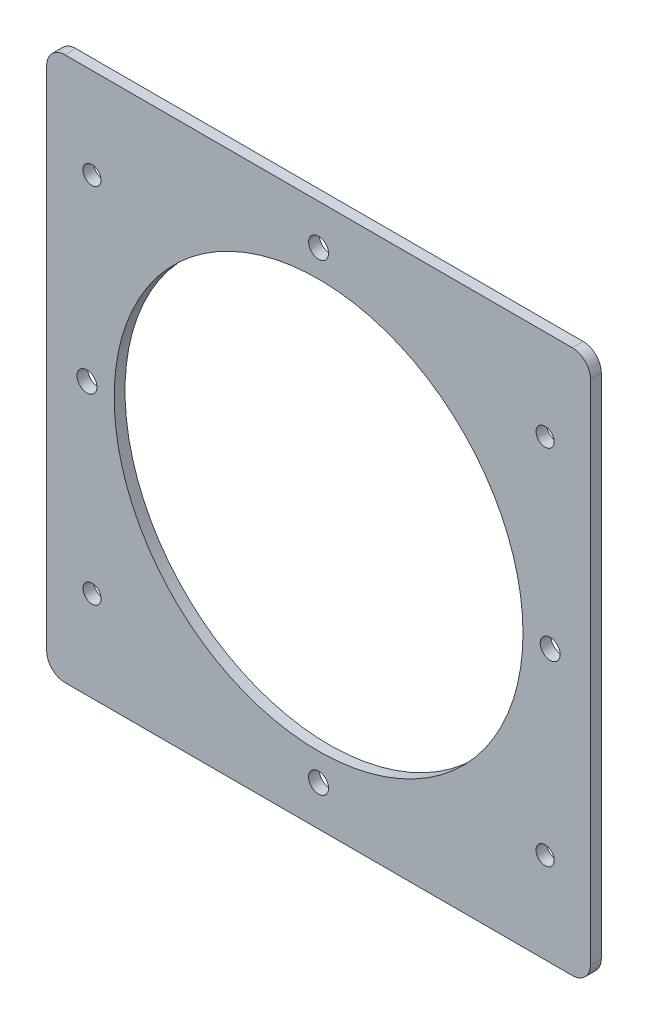
SolidWorks part; units mm, degrees
material "6061 Alloy"
ref_plane "Front Plane" through (0, 0, 0) normal (0, 0, 1) x (1, 0, 0)
ref_plane "Top Plane" through (0, 0, 0) normal (0, 1, 0) x (1, 0, 0)
ref_plane "Right Plane" through (0, 0, 0) normal (1, 0, 0) x (0, 0, -1)
sketch "Sketch1" plane through (0, 0, 0) normal (0, 0, 1) x (1, 0, 0)
  line L1 (-75, 75) -> (75, 75)
  line L2 (-75, 75) -> (-75, -75)
  line L3 (-75, -75) -> (75, -75)
  line L4 (75, 75) -> (75, -75)
  line L5 (0, -75) -> (0, 75) construction
  line L6 (-75, 0) -> (75, 0) construction
  point P0 (0, 0)
  dimension "D1" = 150
  dimension "D2" = 150
extrude "Boss-Extrude1" add sketch "Sketch1" along normal mid plane 3
sketch "Sketch2" plane through (0, 0, 0) normal (0, 0, 1) x (1, 0, 0)
  circle A0 centre (0, 0) radius 63.9 construction
  circle A1 centre (0, 63.9) radius 2.75
  circle A2 centre (63.9, 0) radius 2.75
  circle A3 centre (0, -63.9) radius 2.75
  circle A4 centre (-63.9, 0) radius 2.75
  point P14 (0, 0)
  dimension "D1" = 5.5
  dimension "D2" = 127.8
  dimension "D3" = 4
extrude "Cut-Extrude1" cut sketch "Sketch2" against normal through all both and the other way through all
sketch "Sketch3" plane through (0, 0, 0) normal (0, 0, 1) x (1, 0, 0)
  arc A0 (-56, -6.7052) -> (56, -6.7052) centre (0, 0) ccw
  arc A1 (56, -6.7052) -> (-56, -6.7052) centre (0, 0) ccw
  dimension "D1" = 112.8
extrude "Cut-Extrude2" cut sketch "Sketch3" against normal through all both and the other way through all
sketch "Sketch4" plane through (0, 0, 0) normal (0, 0, 1) x (1, 0, 0)
  line L0 (-75, 75) -> (-75, -75) construction
  line L1 (1.65, 0) -> (-1.65, 0) construction
  line L2 (0, -1.65) -> (0, 1.65) construction
  circle A0 centre (-62.5, 50) radius 2.5
  circle A4 centre (-62.5, -50) radius 2.5
  circle A5 centre (62.5, -50) radius 2.5
  circle A6 centre (62.5, 50) radius 2.5
  dimension "D1" = 5
  dimension "D3" = 50
  dimension "D2" = 12.5
extrude "Cut-Extrude3" cut sketch "Sketch4" against normal through all both and the other way through all
sketch "Sketch10" plane through (75, 0, 0) normal (-1, 0, 0) x (0, 0, 1)
  line L1 (-1.5, 75) -> (1.5, 75)
  line L2 (-1.5, 75) -> (-1.5, -75)
  line L3 (-1.5, -75) -> (1.5, -75)
  line L4 (1.5, 75) -> (1.5, -75)
fillet "Fillet1" radius 5 4 edges at (75, -75, 0) (-75, -75, 0) (75, 75, 0) (-75, 75, 0)
